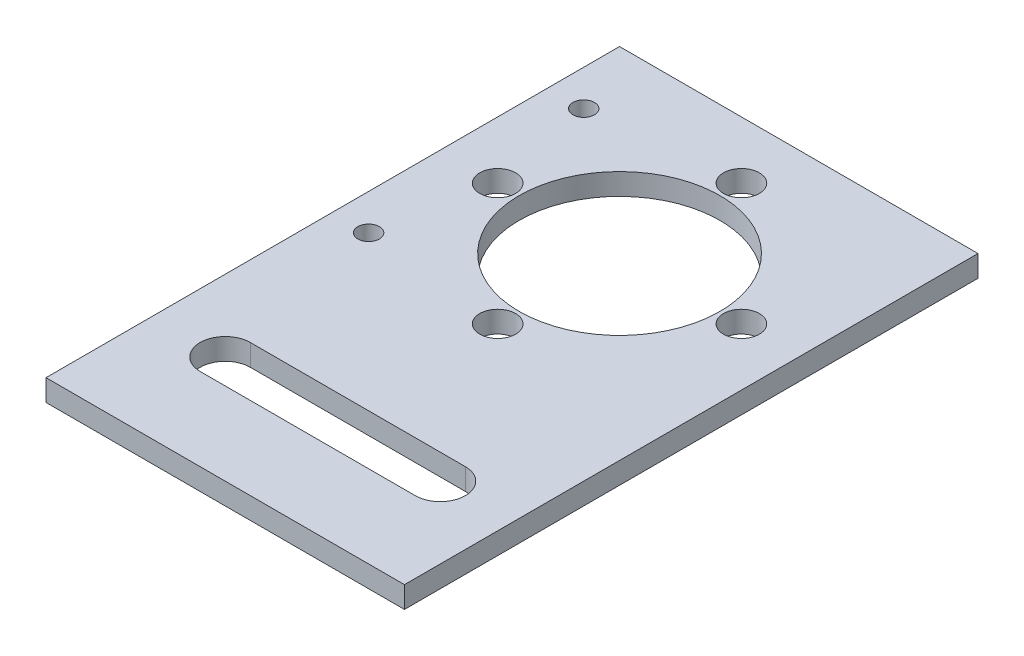
SolidWorks part; units mm, degrees
ref_plane "Front Plane" through (0, 0, 0) normal (0, 0, 1) x (1, 0, 0)
ref_plane "Top Plane" through (0, 0, 0) normal (0, 1, 0) x (1, 0, 0)
ref_plane "Right Plane" through (0, 0, 0) normal (1, 0, 0) x (0, 0, -1)
sketch "Sketch1" plane through (0, 0, 0) normal (0, 1, 0) x (1, 0, 0)
  line L0 (-15, -25) -> (15, -25) construction
  line L1 (-25, 40) -> (25, 40)
  line L2 (-25, 40) -> (-25, -40)
  line L3 (-25, -40) -> (25, -40)
  line L4 (25, 40) -> (25, -40)
  line L5 (-25, 40) -> (25, -40) construction
  line L6 (-25, -40) -> (25, 40) construction
  line L7 (-15, -21.5) -> (15, -21.5)
  line L8 (-15, -28.5) -> (15, -28.5)
  circle A0 centre (0, 15) radius 17 construction
  circle A1 centre (0, 32) radius 2.5
  circle A2 centre (17, 15) radius 2.5
  circle A3 centre (0, -2) radius 2.5
  circle A4 centre (-17, 15) radius 2.5
  arc A5 (-15, -21.5) -> (-15, -28.5) centre (-15, -25) ccw
  arc A6 (15, -28.5) -> (15, -21.5) centre (15, -25) ccw
  circle A7 centre (0, 15) radius 14
  point P0 (0, 0)
  point P8 (0, -25)
  dimension "D1" = 34
  dimension "D5" = 5
  dimension "D7" = 3.5
  dimension "D10" = 28
  dimension "D2" = 15
  dimension "D3" = 80
  dimension "D4" = 50
  dimension "D8" = 15
  dimension "D9" = 30
  dimension "D6" = 4
extrude "Boss-Extrude1" add sketch "Sketch1" along normal blind 3
sketch "Sketch2" plane through (0, 3, 0) normal (0, 1, 0) x (1, 0, 0)
  line L1 (-25, 40) -> (-25, -40) construction
  circle A1 centre (-20, 30) radius 1.5
  circle A2 centre (-20, 0) radius 1.5
  circle A3 centre (0, 15) radius 14 construction
  dimension "D1" = 30
  dimension "D2" = 5
  dimension "D3" = 3
  dimension "D4" = 15
extrude "Cut-Extrude1" cut sketch "Sketch2" against normal blind 10
